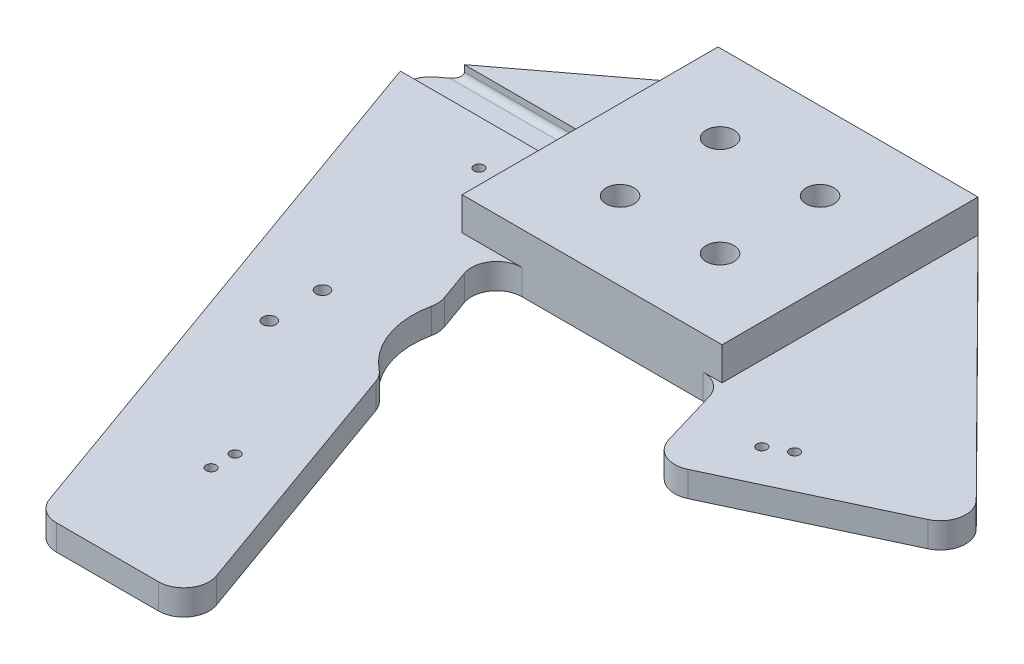
SolidWorks part; units mm, degrees
material "6061 Alloy"
ref_plane "Front" through (0, 0, 0) normal (0, 0, 1) x (1, 0, 0)
ref_plane "Top" through (0, 0, 0) normal (0, 1, 0) x (1, 0, 0)
ref_plane "Right" through (0, 0, 0) normal (1, 0, 0) x (0, 0, -1)
sketch "Sketch1" plane through (0, 0, 0) normal (0, 1, 0) x (1, 0, 0)
  line L0 (0, 32) -> (0, -32) construction
  line L1 (-32.5, 32) -> (32.5, 32)
  line L2 (-32.5, 32) -> (-32.5, -32)
  line L3 (-32.5, -32) -> (32.5, -32)
  line L4 (32.5, 32) -> (32.5, -32)
  dimension "D1" = 64
  dimension "D2" = 65
extrude "Extrude1" add sketch "Sketch1" along normal blind 8.255
sketch "Sketch3" plane through (0, 0, 0) normal (0, -1, 0) x (1, 0, 0)
  line L0 (-32.5, -32) -> (-76.4841, 1.2513)
  line L2 (-76.4841, 1.2513) -> (-24.8776, 145.5121)
  line L3 (-24.8776, 145.5121) -> (14.1128, 145.5121)
  line L4 (-32.5, 32) -> (32.5, 32) construction
  line L5 (40.2655, 58.1158) -> (32.5, 32)
  line L6 (-26.4939, 32) -> (32.5, 32)
  line L7 (14.1128, 145.5121) -> (-26.4939, 32)
  line L8 (40.2655, 58.1158) -> (96.0081, 32)
  line L9 (96.0081, 32) -> (32.5, -32)
  line L10 (32.5, -32) -> (-32.5, -32)
  dimension "D1" = 113.5121
extrude "Extrude2" add sketch "Sketch3" along normal blind 6.35
fillet "Fillet1" radius 6.35 7 edges at (96.0081, -3.175, 32) (40.2655, -3.175, 58.1158) (32.5, -3.175, 32) (-76.4841, -3.175, 1.2513) (-24.8776, -3.175, 145.5121) (14.1128, -3.175, 145.5121)
hole_wizard "CBORE for M6 SBHCS1" positions "Sketch5" profile "Sketch4" counterbore size "M6" standard "Ansi Metric" end condition through all
sketch "Sketch5" plane through (0, -6.35, 0) normal (0, -1, 0) x (1, 0, 0)
  circle A0 centre (-12.5, 12.5) radius 2.5 construction
  circle A1 centre (12.5, 12.5) radius 3 construction
  circle A2 centre (-12.5, -12.5) radius 2.5 construction
  circle A3 centre (12.5, -12.5) radius 2.5 construction
  point P0 (-12.5, 12.5)
  point P1 (12.5, 12.5)
  point P3 (12.5, -12.5)
  point P5 (-12.5, -12.5)
sketch "Sketch4" plane through (-12.5, -6.35, 12.5) normal (1, 0, 0) x (0, 0, -1)
  line L0 (0, 0) -> (0, 14.605)
  line L1 (0, 14.605) -> (3.5, 14.605)
  line L3 (3.5, 14.605) -> (3.5, 8.38)
  line L4 (3.5, 8.38) -> (5.75, 8.38)
  line L5 (5.75, 8.38) -> (5.75, 0)
  line L7 (5.75, 0) -> (0, 0)
  line L11 (0, -6.35) -> (0, 107.95) construction
  dimension "Thru Hole Dia." = 7
  dimension "Thru Hole Depth" = 14.605
  dimension "C'Bore Dia." = 11.5
  dimension "C'Bore Depth" = 8.38
hole_wizard "M3x0.5 Tapped Hole1" positions "Sketch7" profile "Sketch6" tap size "M3x0.5" standard "Ansi Metric" end condition through all
sketch "Sketch7" plane through (0, -6.35, 0) normal (0, -1, 0) x (1, 0, 0)
  line L0 (-11.4807, 111.2595) -> (-14.5033, 111.2595) construction
  line L1 (-11.4807, 103.322) -> (-11.4807, 119.197) construction
  line L2 (-14.5033, 103.322) -> (-14.5033, 119.197) construction
  line L4 (54.665, 40.6748) -> (53.1537, 38.0572) construction
  line L5 (47.7909, 44.6436) -> (61.539, 36.7061) construction
  line L6 (46.2796, 42.0259) -> (60.0277, 34.0884) construction
  line L8 (-41.0473, 16.0657) -> (-42.5586, 18.6833) construction
  line L9 (-34.1732, 20.0344) -> (-47.9214, 12.0969) construction
  line L10 (-35.6845, 22.6521) -> (-49.4327, 14.7146) construction
  line L15 (-12.992, 119.197) -> (-12.992, 103.322) construction
  line L16 (47.0352, 43.3347) -> (60.7834, 35.3972) construction
  line L18 (-48.677, 13.4058) -> (-34.9289, 21.3433) construction
  point P53 (-12.992, 114.2595)
  point P55 (-12.992, 108.2595)
  point P66 (51.3112, 40.866)
  point P68 (56.5074, 37.866)
  point P78 (-39.2049, 18.8745)
  point P80 (-44.401, 15.8745)
  dimension "D1" = 3
  dimension "D2" = 6
  dimension "D3" = 3
  dimension "D4" = 6
  dimension "D5" = 3
  dimension "D6" = 6
sketch "Sketch6" plane through (-12.992, -6.35, 114.2595) normal (1, 0, 0) x (0, 0, -1)
  line L0 (0, 0) -> (0, 14.605)
  line L1 (0, 14.605) -> (1.25, 14.605)
  line L2 (1.25, 14.605) -> (1.25, 0)
  line L5 (1.25, 0) -> (0, 0)
  line L11 (0, -6.35) -> (0, 107.95) construction
  dimension "Thru Tap Drill Dia." = 2.5
  dimension "Thru Tap Drill Depth" = 14.605
cosmetic thread "Hole Thread1" parameters "D2"=3
cosmetic thread "Hole Thread2" parameters "D2"=3
cosmetic thread "Hole Thread3" parameters "D2"=3
cosmetic thread "Hole Thread4" parameters "D2"=3
cosmetic thread "Hole Thread5" parameters "D2"=3
cosmetic thread "Hole Thread6" parameters "D2"=3
hole_wizard "M4x0.7 Tapped Hole1" positions "Sketch9" profile "Sketch8" tap size "M4x0.7" standard "Ansi Metric" end condition through all
sketch "Sketch9" plane through (0, 0, 0) normal (0, 1, 0) x (-1, 0, 0)
  point P1 (37.5352, 75.1386)
  point P4 (37.5352, 61.8689)
sketch "Sketch8" plane through (-37.5352, 0, 75.1386) normal (1, 0, 0) x (0, 0, 1)
  line L0 (0, 0) -> (0, 6.35)
  line L1 (0, 6.35) -> (1.65, 6.35)
  line L2 (1.65, 6.35) -> (1.65, 0)
  line L5 (1.65, 0) -> (0, 0)
  line L11 (0, -6.35) -> (0, 107.95) construction
  dimension "Thread Major Dia." = 3.3
  dimension "Thru Tap Drill Depth" = 6.35
sketch "Sketch10" plane through (0, 0, 0) normal (0, 1, 0) x (1, 0, 0)
  line L0 (-32.5, 32) -> (-32.5, -32) construction
  line L1 (-32.5, 4.6958) -> (-77.6575, 4.6958)
  line L2 (-32.5, 4.6958) -> (-32.5, -4.7022)
  line L3 (-32.5, -4.7022) -> (-77.6575, -4.7022)
  line L4 (-77.6575, 4.6958) -> (-77.6575, -4.7022)
  line L5 (-77.6575, -0.0032) -> (-32.5, -0.0032) construction
  line L6 (-184.3307, -0.0032) -> (-84.3307, -0.0032) construction
  dimension "D1" = 9.398
extrude "Cut-Extrude1" cut sketch "Sketch10" against normal blind 3.175
fillet "Fillet2" radius 1.5875 5 edges at (-53.8351, -3.175, 4.7022) (-50.5587, -3.175, -4.6958) (-32.5, -1.5875, -4.6958) (-32.5, -1.5875, 4.7022) (-32.5, -3.175, 0.0032)
sketch "Sketch11" plane through (0, 0, 0) normal (0, 1, 0) x (-1, 0, 0)
  circle A0 centre (0.2952, 56) radius 20.5885
extrude "Cut-Extrude2" cut sketch "Sketch11" against normal through all
fillet "Fillet3" radius 6.35 2 edges at (-20.0197, -3.175, 50.0981) (-11.8006, -3.175, 73.0738)
